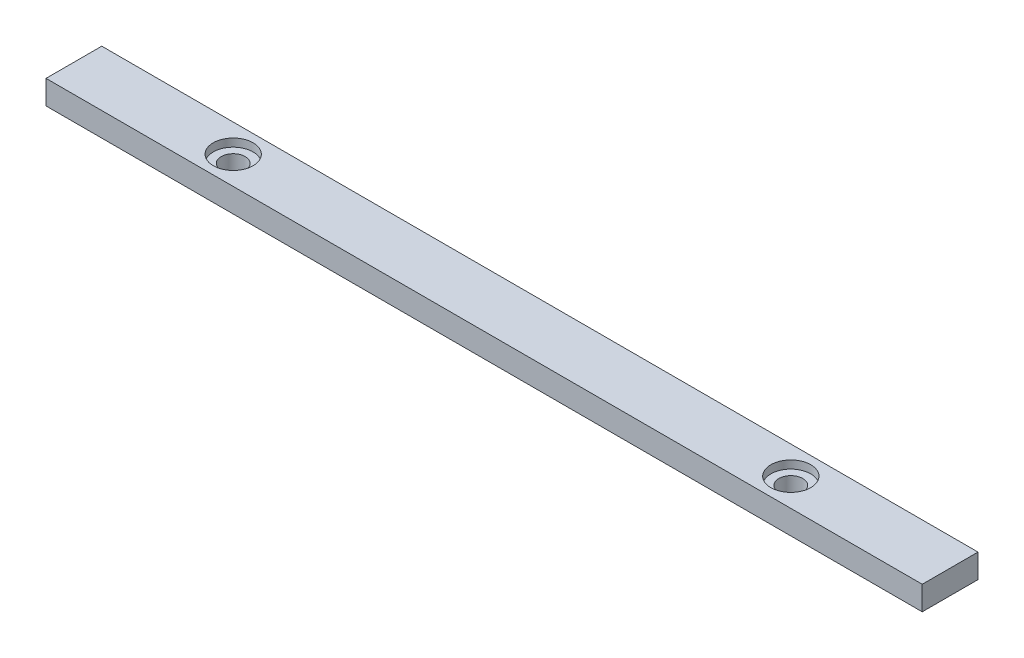
SolidWorks part; units mm, degrees
ref_plane "Front Plane" through (0, 0, 0) normal (0, 0, 1) x (1, 0, 0)
ref_plane "Top Plane" through (0, 0, 0) normal (0, 1, 0) x (1, 0, 0)
ref_plane "Right Plane" through (0, 0, 0) normal (1, 0, 0) x (0, 0, -1)
sketch "Sketch1" plane through (0, 0, 0) normal (0, 1, 0) x (1, 0, 0)
  line L1 (0, 0) -> (110, 0)
  line L2 (0, 0) -> (0, 7)
  line L3 (0, 7) -> (110, 7)
  line L4 (110, 0) -> (110, 7)
  circle A0 centre (20, 3.5) radius 1.5
  circle A1 centre (90, 3.5) radius 1.5
  dimension "D3" = 3
  dimension "D4" = 3
  dimension "D7" = 3.5
  dimension "D1" = 110
  dimension "D2" = 7
  dimension "D5" = 20
  dimension "D6" = 20
  dimension "D8" = 3.5
extrude "Boss-Extrude1" add sketch "Sketch1" along normal blind 3
sketch "Sketch2" plane through (0, 3, 0) normal (0, 1, 0) x (1, 0, 0)
  circle A0 centre (20, 3.5) radius 2.5
  circle A1 centre (90, 3.5) radius 2.5
  dimension "D1" = 5
  dimension "D2" = 5
extrude "Cut-Extrude1" cut sketch "Sketch2" against normal blind 1
